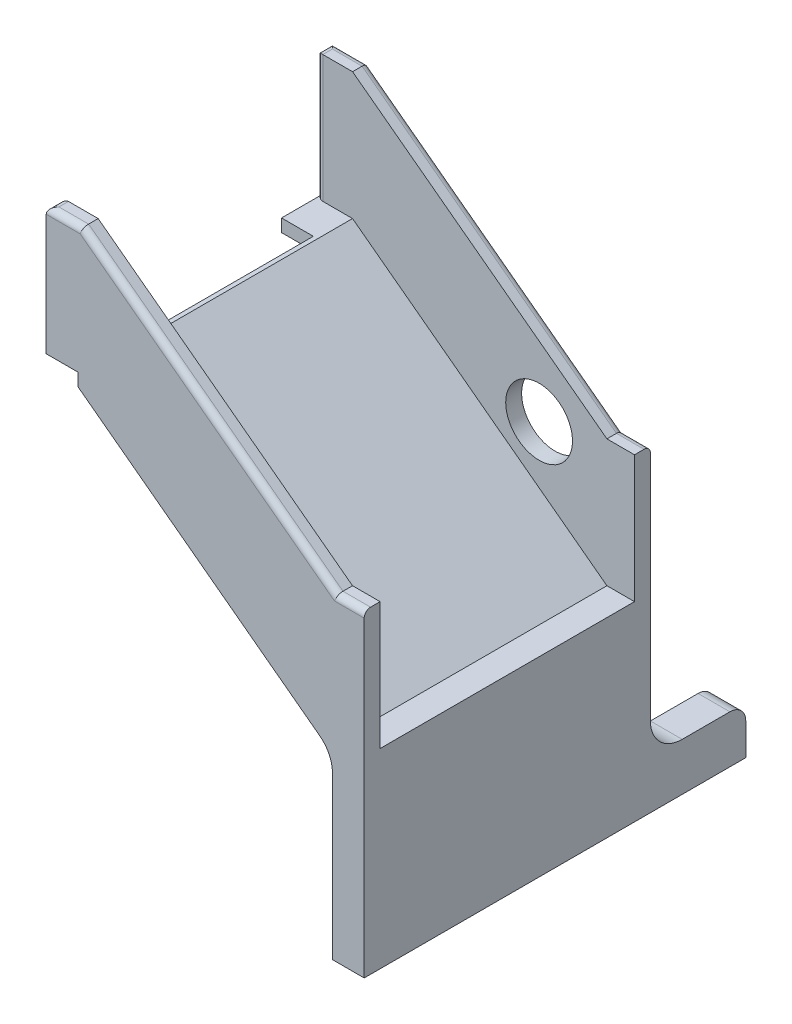
SolidWorks part; units mm, degrees
ref_plane "Front Plane" through (0, 0, 0) normal (0, 0, 1) x (1, 0, 0)
ref_plane "Top Plane" through (0, 0, 0) normal (0, 1, 0) x (1, 0, 0)
ref_plane "Right Plane" through (0, 0, 0) normal (1, 0, 0) x (0, 0, -1)
sketch "Sketch1" plane through (0, 0, 0) normal (0, 0, 1) x (1, 0, 0)
  line L0 (-38.322, 0) -> (41.678, 0) construction
  line L1 (41.678, 0) -> (-38.322, 60)
  line L2 (-38.322, 60) -> (-38.322, 0) construction
  line L3 (-38.322, 60) -> (-48.322, 60)
  line L4 (-48.322, 60) -> (-48.322, 64)
  line L5 (-48.322, 64) -> (-36.9887, 64)
  line L6 (-36.9887, 64) -> (43.0113, 4)
  line L7 (43.0113, 4) -> (51.678, 4)
  line L8 (51.678, 4) -> (51.678, 0)
  line L9 (51.678, 0) -> (41.678, 0)
  dimension "D1" = 80
  dimension "D2" = 60
  dimension "D3" = 4
  dimension "D4" = 4
  dimension "D5" = 4
  dimension "D6" = 10
  dimension "D7" = 10
extrude "Boss-Extrude1" add sketch "Sketch1" along normal mid plane 90
sketch "Sketch2" plane through (0, 0, 45) normal (0, 0, 1) x (1, 0, 0)
  line L0 (-48.322, 64) -> (-48.322, 104)
  line L1 (-48.322, 104) -> (-36.9887, 104)
  line L2 (-36.9887, 104) -> (43.0113, 44)
  line L3 (43.0113, 44) -> (51.678, 44)
  line L4 (51.678, 44) -> (51.678, 4)
  line L5 (51.678, 4) -> (43.0113, 4)
  line L6 (43.0113, 4) -> (-36.9887, 64)
  line L7 (-36.9887, 64) -> (-48.322, 64)
  dimension "D1" = 40
extrude "Boss-Extrude2" add sketch "Sketch2" against normal blind 5
mirror "Mirror1" about plane through (0, 0, 0) normal (0, 0, 1) of "Boss-Extrude2"
sketch "Sketch3" plane through (0, 0, -45) normal (0, 0, -1) x (-1, 0, 0)
  line L0 (-51.678, 0) -> (-51.678, 44) construction
  line L1 (-41.678, 0) -> (-51.678, 0) construction
  circle A0 centre (-21.678, 38) radius 10.5
  dimension "D1" = 21
  dimension "D2" = 30
  dimension "D3" = 38
extrude "Cut-Extrude1" cut sketch "Sketch3" against normal up to next
sketch "Sketch8" plane through (0, 0, 45) normal (0, 0, 1) x (1, 0, 0)
  line L0 (41.678, 0) -> (51.678, 0)
  line L1 (51.678, 0) -> (51.678, -56)
  line L2 (41.678, 0) -> (41.678, -56)
  line L3 (41.678, -56) -> (51.678, -56)
  dimension "D1" = 56
extrude "Boss-Extrude4" add sketch "Sketch8" against normal blind 90
fillet "Fillet2" radius 10 1 edges at (41.678, 0, 0)
fillet "Fillet3" radius 2 10 edges at (47.3446, 44, 45) (47.3446, 44, -45) (-42.6554, 104, -45) (3.0113, 74, -45) (3.0113, 74, 45) (-42.6554, 104, 45) (-48.322, 104, -42.5) (-48.322, 104, 42.5) (-48.322, 84, -40) (-48.322, 84, 40)
sketch "Sketch9" plane through (0, 0, 45) normal (0, 0, 1) x (1, 0, 0)
  line L1 (-48.322, 60) -> (-38.322, 60)
  line L2 (-48.322, 60) -> (-48.322, 64)
  line L3 (-48.322, 64) -> (-38.322, 64)
  line L4 (-38.322, 60) -> (-38.322, 64)
  dimension "D1" = 10
  dimension "D2" = 4
extrude "Cut-Extrude2" cut sketch "Sketch9" against normal blind 74
sketch "Sketch10" plane through (-38.322, 0, 0) normal (-1, 0, 0) x (0, 0, 1)
  line L0 (45, 60) -> (-29, 60) construction
  line L1 (-1.42, 60) -> (13.58, 60)
  line L2 (-1.42, 60) -> (-1.42, 25)
  line L3 (-1.42, 25) -> (13.58, 25)
  line L4 (13.58, 60) -> (13.58, 25)
  circle A0 centre (6.08, 44) radius 2.9
  point P6 (6.08, 60)
  dimension "D4" = 5.8
  dimension "D1" = 51.08
  dimension "D2" = 15
  dimension "D3" = 35
  dimension "D5" = 16
extrude "Boss-Extrude5" add sketch "Sketch10" against normal blind 5 separate body
sketch "Sketch11" plane through (0, 0, -45) normal (0, 0, -1) x (-1, 0, 0)
  line L0 (-41.678, -5) -> (-41.678, -56) construction
  line L1 (-51.678, -56) -> (-41.678, -56)
  line L2 (-51.678, -56) -> (-51.678, -41)
  line L3 (-51.678, -41) -> (-41.678, -41)
  line L4 (-41.678, -56) -> (-41.678, -41)
  dimension "D1" = 15
extrude "Boss-Extrude6" add sketch "Sketch11" along normal blind 30
fillet "Fillet4" radius 10 1 edges at (46.678, -41, -45)
fillet "Fillet5" radius 5 1 edges at (46.678, -41, -75)
